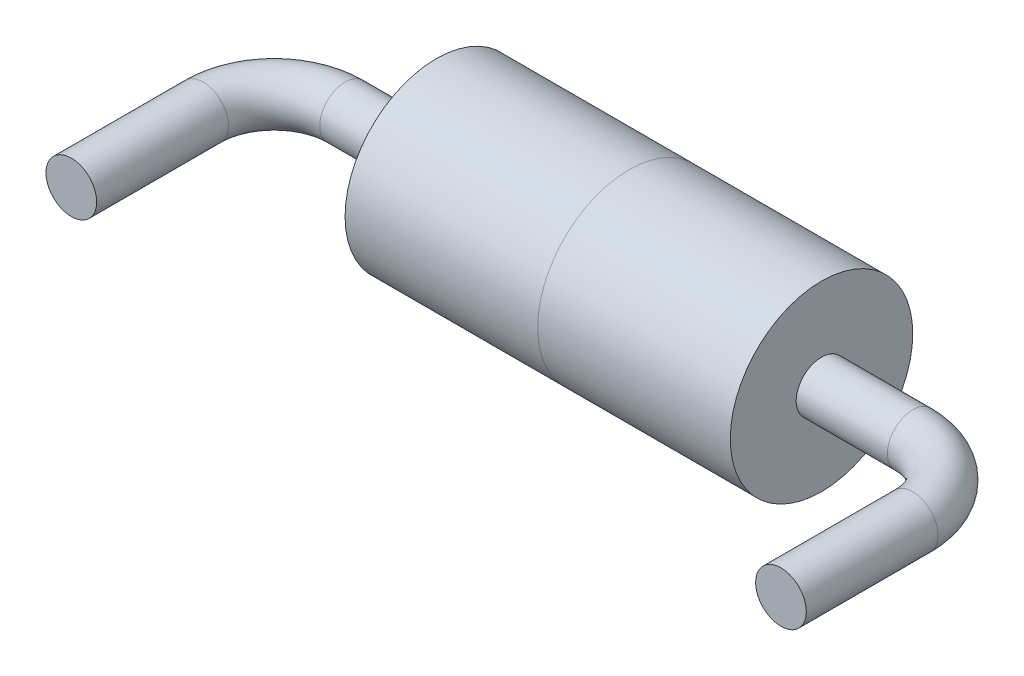
SolidWorks part; units mm, degrees
ref_plane "Спереди" through (0, 0, 0) normal (0, 0, 1) x (1, 0, 0)
ref_plane "Сверху" through (0, 0, 0) normal (0, 1, 0) x (1, 0, 0)
ref_plane "Справа" through (0, 0, 0) normal (1, 0, 0) x (0, 0, -1)
sketch "Эскиз1" plane through (0, 0, 0) normal (0, 1, 0) x (1, 0, 0)
  line L0 (-0.7, 0) -> (-6.3, 0)
  line L1 (-7, -0.7) -> (-7, -2)
  line L2 (0, -0.7) -> (0, -2)
  arc A0 (-6.3, 0) -> (-7, -0.7) centre (-6.3, -0.7) ccw
  arc A1 (0, -0.7) -> (-0.7, 0) centre (-0.7, -0.7) ccw
  point P9 (0, 0)
  dimension "D1" = 0.7
  dimension "D2" = 0.7
ref_plane "Плоскость1" through (0, 0, 2) normal (0, 0, 1) x (1, 0, 0)
sketch "Эскиз2" plane through (0, 0, 2) normal (0, 0, 1) x (1, 0, 0)
  circle A0 centre (0, 0) radius 0.25
sweep "По траектории1" add profiles "Эскиз2" path "Эскиз1"
sketch "Эскиз6" plane through (0, 0, 0) normal (0, 1, 0) x (1, 0, 0)
  line L0 (-3.5, 0) -> (-5.4, 0)
  line L6 (-3.5, 0) -> (-1.6, 0)
ref_plane "Плоскость2" through (-5.4, 0, 0) normal (1, 0, 0) x (0, 0, -1)
sketch "Эскиз7" plane through (-5.4, 0, 0) normal (1, 0, 0) x (0, 0, -1)
  circle A0 centre (0, 0) radius 0.9
sweep "По траектории2" add profiles "Эскиз7" path "Эскиз6"
